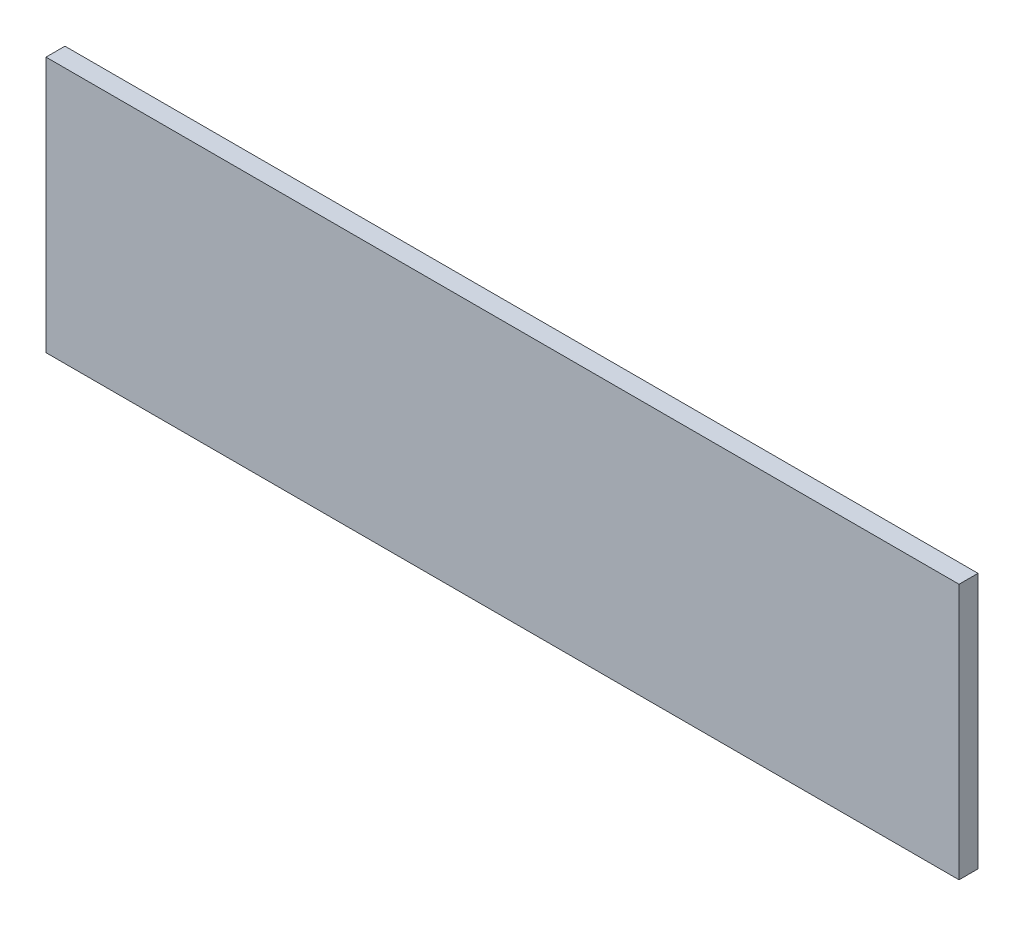
SolidWorks part; units mm, degrees
material "AISI 316 Нержавеющая сталь, лист (SS)"
ref_plane "Спереди" through (0, 0, 0) normal (0, 0, 1) x (1, 0, 0)
ref_plane "Сверху" through (0, 0, 0) normal (0, 1, 0) x (1, 0, 0)
ref_plane "Справа" through (0, 0, 0) normal (1, 0, 0) x (0, 0, -1)
sketch "Эскиз1" plane through (0, 0, 0) normal (0, 0, 1) x (1, 0, 0)
  line L1 (0, 0) -> (159, 0)
  line L2 (0, 0) -> (0, 44.58)
  line L3 (0, 44.58) -> (159, 44.58)
  line L4 (159, 0) -> (159, 44.58)
  dimension "D1" = 44.58
  dimension "D2" = 159
extrude "Бобышка-Вытянуть1" add sketch "Эскиз1" along normal blind 3.3
